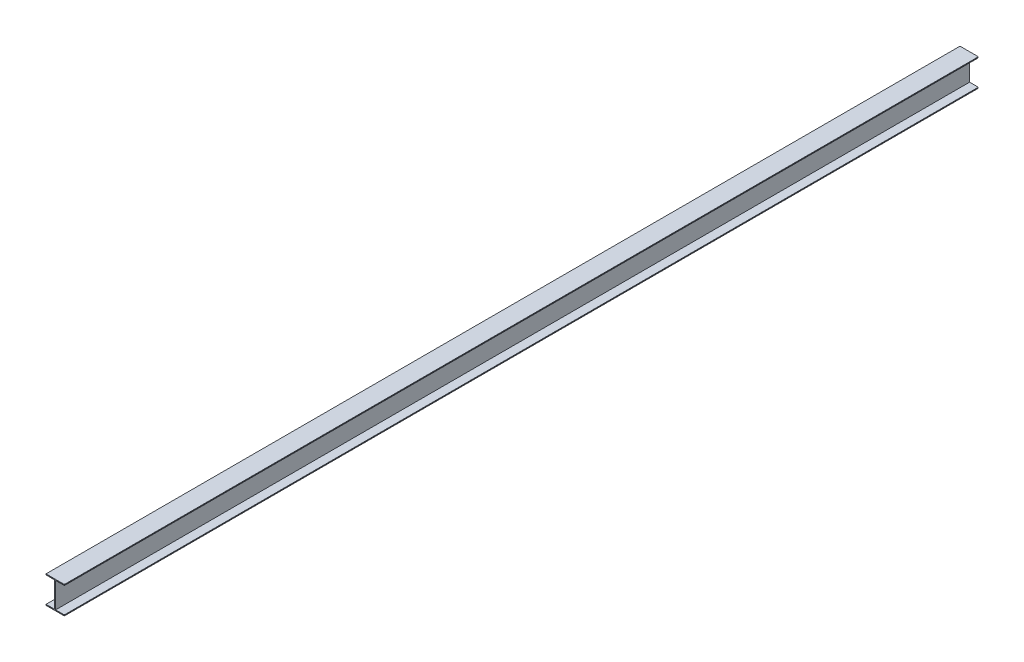
SolidWorks part; units mm, degrees
material "ASTM A992 Steel"
ref_plane "Front" through (0, 0, 0) normal (0, 0, 1) x (1, 0, 0)
ref_plane "Top" through (0, 0, 0) normal (0, 1, 0) x (1, 0, 0)
ref_plane "Right" through (0, 0, 0) normal (1, 0, 0) x (0, 0, -1)
sketch "Sketch1" plane through (0, 0, 0) normal (0, 0, 1) x (1, 0, 0)
  line L0 (0, -0.0002) -> (101.6, -0.0002)
  line L1 (101.6, -0.0002) -> (101.6, -7.1122)
  line L2 (101.6, -7.1122) -> (53.408, -7.1122)
  line L3 (53.408, -7.1122) -> (53.408, -146.0502)
  line L4 (53.408, -146.0502) -> (101.6, -146.0502)
  line L5 (101.6, -146.0502) -> (101.6, -153.1622)
  line L6 (101.6, -153.1622) -> (0, -153.1622)
  line L7 (0, -153.1622) -> (0, -146.0502)
  line L8 (0, -146.0502) -> (47.566, -146.0502)
  line L9 (47.566, -146.0502) -> (47.566, -7.1122)
  line L10 (47.566, -7.1122) -> (0, -7.1122)
  line L11 (0, -7.1122) -> (0, -0.0002)
  line L12 (50.8, -0.0002) -> (50.8, -153.1622) construction
  dimension "D1" = 5.842
  dimension "D2" = 7.112
  dimension "D3" = 7.112
  dimension "D4" = 7.112
  dimension "D5" = 153.162
  dimension "D6" = 50.8
  dimension "D7" = 50.8
  dimension "D8" = 47.566
extrude "Boss-Extrude1" add sketch "Sketch1" along normal blind 5062
sketch "Sketch2" plane through (0, -153.1622, 0) normal (0, -1, 0) x (1, 0, 0)
  line L0 (0, 5062) -> (0, 0) construction
  line L1 (101.6, 5062) -> (101.6, 0) construction
  line L3 (101.6, 2531) -> (101.6, 2683.4)
  line L4 (101.6, 2683.4) -> (-279.5172, 2683.4)
  line L5 (-279.5172, 2607.2) -> (-279.5172, 2683.4)
  line L8 (101.6, 2531) -> (101.6, 2378.6)
  line L9 (101.6, 2378.6) -> (-279.5172, 2378.6)
  line L10 (-279.5172, 2607.2) -> (-279.5172, 2378.6)
  point P0 (0, 2531)
  dimension "D1" = 152.4
  dimension "D2" = 152.4
split line "Split Line1"
fillet "Fillet1" radius 3.175 4 edges at (101.6, -3.5562, 5062) (101.6, -149.6062, 5062) (101.6, -149.6062, 0) (101.6, -3.5562, 0)
fillet "Fillet2" radius 3.175 11 edges at (0, -153.1622, 1189.3) (0, -153.1622, 2531) (0, -153.1622, 3872.7) (49.2125, -153.1622, 0) (100.6701, -153.1622, 0.9299) (101.6, -153.1622, 1190.8875) (101.6, -153.1622, 3871.1125) (101.6, -153.1622, 2607.2) (101.6, -153.1622, 2454.8) (100.6701, -153.1622, 5061.0701) (49.2125, -153.1622, 5062)
fillet "Fillet3" radius 3.175 8 edges at (75.9165, -7.1122, 0) (100.6701, -7.1122, 0.9299) (101.6, -7.1122, 2531) (100.6701, -7.1122, 5061.0701) (23.783, -7.1122, 0) (0, -7.1122, 2531) (75.9165, -7.1122, 5062) (23.783, -7.1122, 5062)
sketch "Sketch3" plane through (0, 0, 0) normal (0, 0, -1) x (-1, 0, 0)
  line L12 (-98.425, -0.0002) -> (-98.425, -3.9372)
  line L13 (-98.425, -3.9372) -> (-53.408, -3.9372)
  line L14 (-53.408, -3.9372) -> (-53.408, -146.0502)
  line L15 (-53.408, -146.0502) -> (-98.425, -146.0502)
  line L16 (-98.425, -146.0502) -> (-98.425, -149.9872)
  line L17 (-98.425, -149.9872) -> (0, -149.9872)
  line L18 (0, -149.9872) -> (0, -146.0502)
  line L19 (0, -146.0502) -> (-47.566, -146.0502)
  line L20 (-47.566, -146.0502) -> (-47.566, -3.9372)
  line L21 (-47.566, -3.9372) -> (0, -3.9372)
  line L22 (0, -3.9372) -> (0, -0.0002)
  line L23 (0, -0.0002) -> (-98.425, -0.0002)
  line L24 (-98.425, -0.0002) -> (-98.425, -3.9372)
  line L25 (-98.425, -3.9372) -> (-53.408, -3.9372)
  line L26 (-53.408, -3.9372) -> (-53.408, -146.0502)
  line L27 (-53.408, -146.0502) -> (-98.425, -146.0502)
  line L28 (-98.425, -146.0502) -> (-98.425, -149.9872)
  line L29 (-98.425, -149.9872) -> (0, -149.9872)
  line L30 (0, -149.9872) -> (0, -146.0502)
  line L31 (0, -146.0502) -> (-47.566, -146.0502)
  line L32 (-47.566, -146.0502) -> (-47.566, -3.9372)
  line L33 (-47.566, -3.9372) -> (0, -3.9372)
  line L34 (0, -3.9372) -> (0, -0.0002)
  line L35 (0, -0.0002) -> (-98.425, -0.0002)
  dimension "D1" = 0
extrude "Boss-Extrude3" [suppressed] add sketch "Sketch3" along normal up to body
sketch "Sketch4" plane through (0, 0, 5062) normal (0, 0, 1) x (1, 0, 0)
  line L12 (53.408, -146.0502) -> (53.408, -3.9372)
  line L13 (53.408, -3.9372) -> (98.425, -3.9372)
  line L14 (98.425, -3.9372) -> (98.425, -0.0002)
  line L15 (98.425, -0.0002) -> (0, -0.0002)
  line L16 (0, -0.0002) -> (0, -3.9372)
  line L17 (0, -3.9372) -> (47.566, -3.9372)
  line L18 (47.566, -3.9372) -> (47.566, -146.0502)
  line L19 (47.566, -146.0502) -> (0, -146.0502)
  line L20 (0, -146.0502) -> (0, -149.9872)
  line L21 (0, -149.9872) -> (98.425, -149.9872)
  line L22 (98.425, -149.9872) -> (98.425, -146.0502)
  line L23 (98.425, -146.0502) -> (53.408, -146.0502)
  line L24 (53.408, -146.0502) -> (53.408, -3.9372)
  line L25 (53.408, -3.9372) -> (98.425, -3.9372)
  line L26 (98.425, -3.9372) -> (98.425, -0.0002)
  line L27 (98.425, -0.0002) -> (0, -0.0002)
  line L28 (0, -0.0002) -> (0, -3.9372)
  line L29 (0, -3.9372) -> (47.566, -3.9372)
  line L30 (47.566, -3.9372) -> (47.566, -146.0502)
  line L31 (47.566, -146.0502) -> (0, -146.0502)
  line L32 (0, -146.0502) -> (0, -149.9872)
  line L33 (0, -149.9872) -> (98.425, -149.9872)
  line L34 (98.425, -149.9872) -> (98.425, -146.0502)
  line L35 (98.425, -146.0502) -> (53.408, -146.0502)
  dimension "D1" = 0
extrude "Boss-Extrude4" [suppressed] add sketch "Sketch4" along normal up to body separate body
